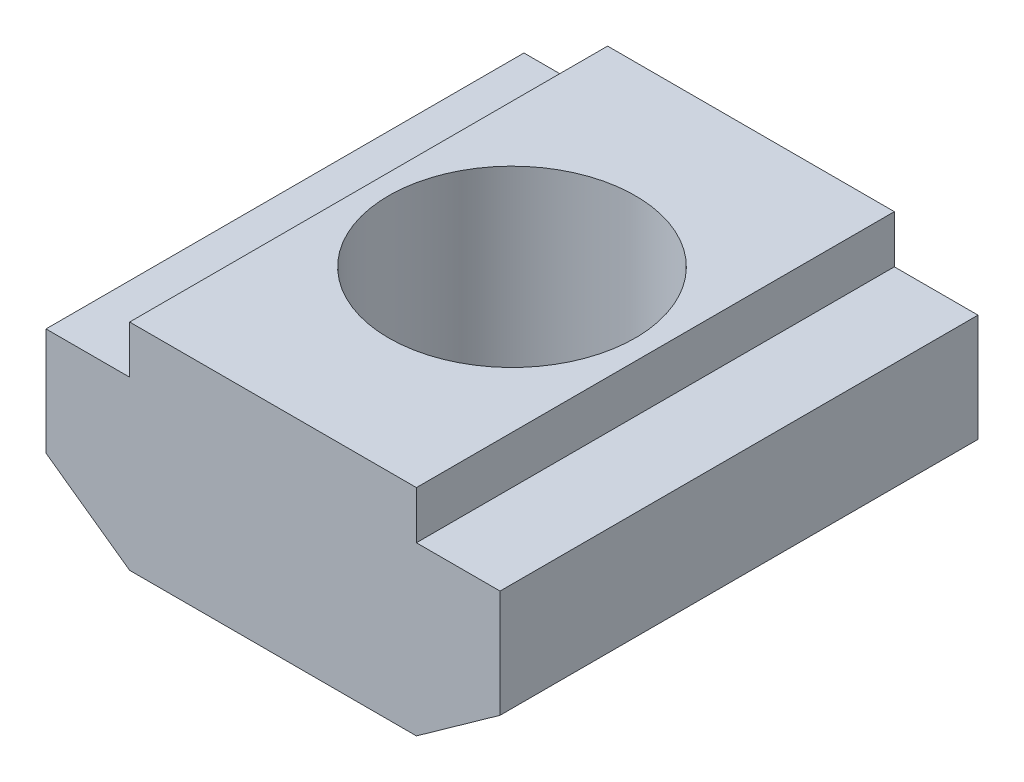
SolidWorks part; units mm, degrees
ref_plane "前视基准面" through (0, 0, 0) normal (0, 0, 1) x (1, 0, 0)
ref_plane "上视基准面" through (0, 0, 0) normal (0, 1, 0) x (1, 0, 0)
ref_plane "右视基准面" through (0, 0, 0) normal (1, 0, 0) x (0, 0, -1)
sketch "草图1" plane through (0, 0, 0) normal (0, 0, 1) x (1, 0, 0)
  line L0 (0, 19.2532) -> (0, -19.7565) construction
  line L1 (-3, 0) -> (3, 0)
  line L2 (3, 0) -> (3, -1)
  line L3 (3, -1) -> (4.75, -1)
  line L4 (4.75, -1) -> (4.75, -3.2517)
  line L5 (4.75, -3.2517) -> (3, -4.5)
  line L6 (3, -4.5) -> (-3, -4.5)
  line L7 (-4.75, -3.2517) -> (-3, -4.5)
  line L8 (-4.75, -1) -> (-4.75, -3.2517)
  line L9 (-3, -1) -> (-4.75, -1)
  line L10 (-3, 0) -> (-3, -1)
  dimension "D1" = 6
  dimension "D2" = 9.5
  dimension "D3" = 1
  dimension "D4" = 4.5
  dimension "D5" = 144.5
  dimension "D6" = 6
extrude "凸台-拉伸1" add sketch "草图1" along normal blind 10
sketch "草图2" plane through (0, 0, 0) normal (0, 1, 0) x (1, 0, 0)
  line L0 (0, 1.0228) -> (0, -10.3101) construction
  line L1 (-5.8897, -5) -> (5.8897, -5) construction
  line L2 (3, 0) -> (-3, 0) construction
  circle A0 centre (0, -5) radius 2.58
  dimension "D2" = 5.16
  dimension "D1" = 5
extrude "切除-拉伸1" cut sketch "草图2" against normal up to next
sketch "草图3" [suppressed] plane through (0, 0, 0) normal (0, 0, 1) x (1, 0, 0)
  line L0 (0, 26.8035) -> (0, -23.0283) construction
  line L1 (-2.7, 0) -> (2.7, 0)
  line L2 (3, -0.3) -> (3, -1)
  line L3 (3, -1) -> (4.43, -1)
  line L4 (4.75, -1.32) -> (4.75, -1.5825)
  line L5 (4.6822, -1.7976) -> (3.0896, -4.0721)
  line L6 (2.8438, -4.2) -> (-2.8438, -4.2)
  line L7 (-4.6822, -1.7976) -> (-3.0896, -4.0721)
  line L8 (-4.75, -1.32) -> (-4.75, -1.5825)
  line L9 (-3, -1) -> (-4.43, -1)
  line L10 (-3, -0.3) -> (-3, -1)
  arc A0 (4.75, -1.5825) -> (4.6822, -1.7976) centre (4.375, -1.5825) cw
  arc A1 (3.0896, -4.0721) -> (2.8438, -4.2) centre (2.8438, -3.9) cw
  arc A2 (4.43, -1) -> (4.75, -1.32) centre (4.43, -1.32) cw
  arc A3 (2.7, 0) -> (3, -0.3) centre (2.7, -0.3) cw
  arc A4 (-2.7, 0) -> (-3, -0.3) centre (-2.7, -0.3) ccw
  arc A5 (-4.43, -1) -> (-4.75, -1.32) centre (-4.43, -1.32) ccw
  arc A6 (-3.0896, -4.0721) -> (-2.8438, -4.2) centre (-2.8438, -3.9) ccw
  arc A7 (-4.75, -1.5825) -> (-4.6822, -1.7976) centre (-4.375, -1.5825) ccw
  point P14 (3, -4.2)
  point P19 (3, 0)
  point P33 (-3, 0)
  point P34 (-3, -4.2)
  dimension "D7" = 0.375
  dimension "D8" = 0.3
  dimension "D9" = 0.32
  dimension "D10" = 0.3
  dimension "D1" = 6
  dimension "D2" = 9.5
  dimension "D3" = 1
  dimension "D4" = 4.2
  dimension "D5" = 6
  dimension "D6" = 125
extrude "凸台-拉伸2" [suppressed] add sketch "草图3" along normal blind 9.5
sketch "草图4" [suppressed] plane through (0, 0, 0) normal (0, 1, 0) x (1, 0, 0)
  line L0 (0, 0) -> (0, -10.055) construction
  line L1 (-5.3369, -4.75) -> (5.4857, -4.75) construction
  line L2 (-3, 0) -> (-4.43, 0) construction
  circle A0 centre (0, -4.75) radius 1.72
  dimension "D2" = 5.16
  dimension "D1" = 4.75
extrude "切除-拉伸2" [suppressed] cut sketch "草图4" against normal up to next
cosmetic thread "装饰螺纹线2" [suppressed] parameters "D2"=6
